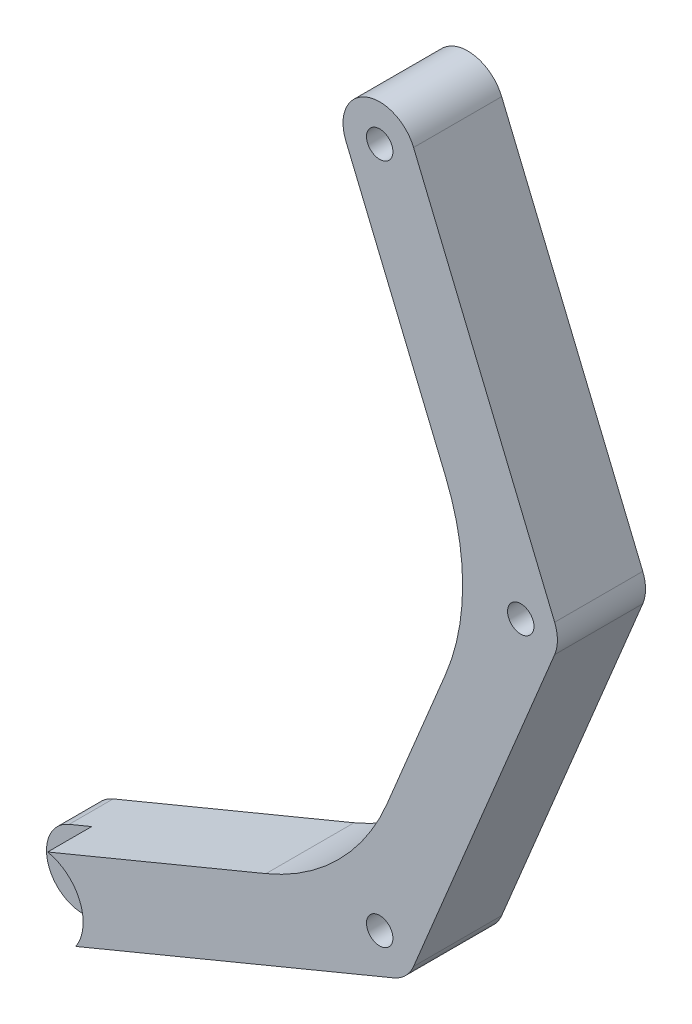
SolidWorks part; units mm, degrees
ref_plane "Front Plane" through (0, 0, 0) normal (0, 0, 1) x (1, 0, 0)
ref_plane "Top Plane" through (0, 0, 0) normal (0, 1, 0) x (1, 0, 0)
ref_plane "Right Plane" through (0, 0, 0) normal (1, 0, 0) x (0, 0, -1)
sketch "Sketch1" plane through (0, 0, 0) normal (0, 0, 1) x (1, 0, 0)
  line L0 (0, -27.3304) -> (18.5294, 17.4035) construction
  line L7 (27.3304, 0) -> (19.3255, 19.3255) construction
  line L13 (0, -27.3304) -> (19.3255, -19.3255) construction
  line L14 (19.3255, -19.3255) -> (27.3304, 0) construction
  line L15 (-23.328, 9.6628) -> (-27.3304, 0) [skipped]
  line L16 (0, 27.3304) -> (-1.922, 26.5343) [skipped]
  line L17 (19.3255, 19.3255) -> (17.4035, 20.1216) [skipped]
  line L18 (-23.328, -9.6628) -> (-19.3255, -19.3255) [skipped]
  line L19 (-1.922, -26.5343) -> (0, -27.3304) [skipped]
  line L20 (21.2476, 20.1216) -> (29.2524, 0.7961)
  line L21 (29.2524, -0.7961) -> (21.2476, -20.1216)
  line L22 (-0.7961, -25.4084) -> (12.8732, -19.7464)
  line L23 (0.7961, -29.2524) -> (20.1216, -21.2476)
  line L25 (17.4035, 18.5294) -> (23.0655, 4.8601)
  line L26 (23.0655, -4.8601) -> (19.7464, -12.8732)
  circle A0 centre (0, 0) radius 25.25 construction
  arc A2 (21.2476, 20.1216) -> (17.4035, 18.5294) centre (19.3255, 19.3255) ccw
  arc A6 (12.8732, -19.7464) -> (19.7464, -12.8732) centre (8.0131, -8.0131) ccw
  arc A7 (23.0655, 4.8601) -> (23.0655, -4.8601) centre (11.3322, 0) cw
  arc A8 (29.2524, -0.7961) -> (29.2524, 0.7961) centre (27.3304, 0) ccw
  arc A9 (20.1216, -21.2476) -> (21.2476, -20.1216) centre (19.3255, -19.3255) ccw
  arc A10 (-0.7961, -25.4084) -> (0.7961, -29.2524) centre (0, -27.3304) ccw
  dimension "D1" = 50.5
  dimension "D2" = 12.7
extrude "Boss-Extrude1" add sketch "Sketch1" along normal blind 5
sketch "Sketch2" plane through (0, 0, 5) normal (0, 0, 1) x (1, 0, 0)
  line L0 (-1.922, -28.1265) -> (0, -27.3304) construction
  arc A2 (-0.7961, -25.4084) -> (0.7961, -29.2524) centre (0, -27.3304) ccw construction
  circle A3 centre (0, -27.3304) radius 2.5
  dimension "D1" = 5
extrude "Cut-Extrude1" cut sketch "Sketch2" against normal blind 2.5
sketch "Sketch3" plane through (0, 0, 2.5) normal (0, 0, 1) x (1, 0, 0)
  circle A0 centre (0, -27.3304) radius 0.75
  dimension "D1" = 1.5
extrude "Cut-Extrude2" cut sketch "Sketch3" against normal through all both and the other way through all
sketch "Sketch4" plane through (0, 0, 0) normal (0, 0, -1) x (-1, 0, 0)
  circle A0 centre (-19.3255, 19.3255) radius 0.75
  circle A1 centre (-27.3304, 0) radius 0.75
  circle A2 centre (-19.3255, -19.3255) radius 0.75
  dimension "D1" = 1.5
  dimension "D2" = 1.5
  dimension "D3" = 1.5
extrude "Cut-Extrude3" cut sketch "Sketch4" against normal through all both and the other way through all
